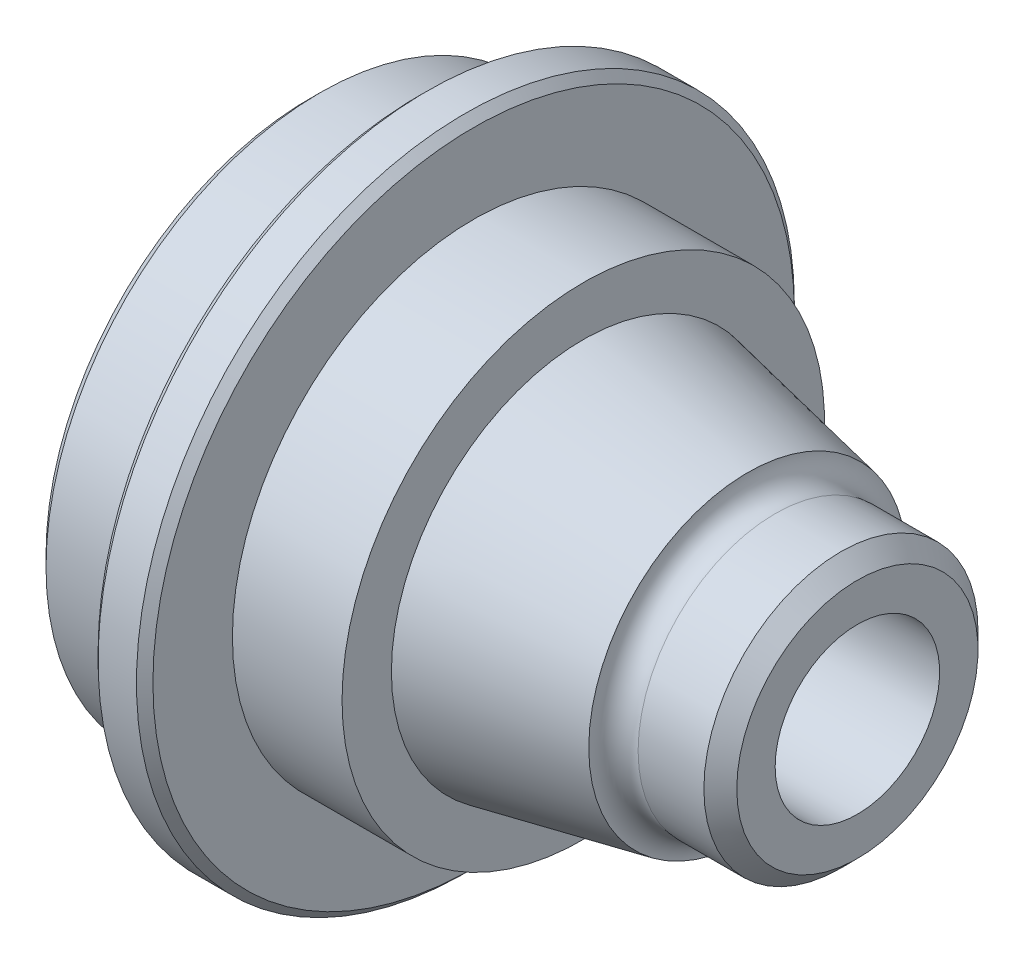
SolidWorks part; units mm, degrees
ref_plane "Piano frontale" through (0, 0, 0) normal (0, 0, 1) x (1, 0, 0)
ref_plane "Piano superiore" through (0, 0, 0) normal (0, 1, 0) x (1, 0, 0)
ref_plane "Piano destro" through (0, 0, 0) normal (1, 0, 0) x (0, 0, -1)
sketch "Schizzo1" plane through (0, 0, 0) normal (0, 0, 1) x (1, 0, 0)
  line L0 (-117.1256, 0) -> (64.9354, 0) construction
  line L1 (-100, 40) -> (-100, 50)
  line L2 (-100, 50) -> (-80, 50)
  line L3 (-80, 50) -> (-80, 60)
  line L4 (-80, 60) -> (-70, 60)
  line L5 (-70, 60) -> (-70, 44)
  line L6 (-70, 44) -> (-50, 44)
  line L7 (-50, 44) -> (-50, 35)
  line L8 (-50, 35) -> (-20, 29)
  line L9 (-15, 25) -> (0, 25)
  line L10 (0, 25) -> (0, 15)
  line L11 (0, 15) -> (-25, 15)
  line L12 (-100, 40) -> (-79, 40)
  line L13 (-79, 40) -> (-79, 42)
  line L14 (-79, 42) -> (-77, 42)
  line L15 (-77, 42) -> (-77, 34)
  line L16 (-79, 40) -> (-79, 0)
  line L17 (0, 25) -> (0, 0) construction
  arc A0 (-20, 29) -> (-15, 25) centre (-16.002, 28.8725) ccw
  arc A1 (-25, 15) -> (-77, 34) centre (-69.2692, -25.4999) ccw
  point P15 (-79, 41)
  point P25 (-80, 55)
  dimension "D1" = 60
  dimension "D2" = 50
  dimension "D17" = 4
  dimension "D3" = 21
  dimension "D4" = 70
  dimension "D5" = 120
  dimension "D6" = 100
  dimension "D7" = 2
  dimension "D8" = 84
  dimension "D9" = 100
  dimension "D10" = 20
  dimension "D11" = 30
  dimension "D12" = 20
  dimension "D13" = 20
  dimension "D14" = 88
  dimension "D15" = 15
  dimension "D16" = 30
  dimension "D18" = 68
  dimension "D19" = 80
  dimension "D20" = 58
  dimension "D21" = 15
  dimension "D22" = 52
revolve "Rivoluzione1" add sketch "Schizzo1" angle 360 about L0
chamfer "Smusso1" distance 2 angle 45 2 edges at (-100, 0, 40) (-100, 0, 50)
fillet "Raccordo1" radius 8 1 edges at (-25, 0, 15)
chamfer "Smusso2" distance 1.5 angle 45 2 edges at (-70, 0, 60) (-80, 0, 60)
chamfer "Smusso3" distance 3 angle 45 1 edges at (0, 0, 25)
sketch "Schizzo2" plane through (-100, 0, 0) normal (-1, 0, 0) x (0, 0, 1)
  line L0 (0, 0) -> (0, 63.7066)
